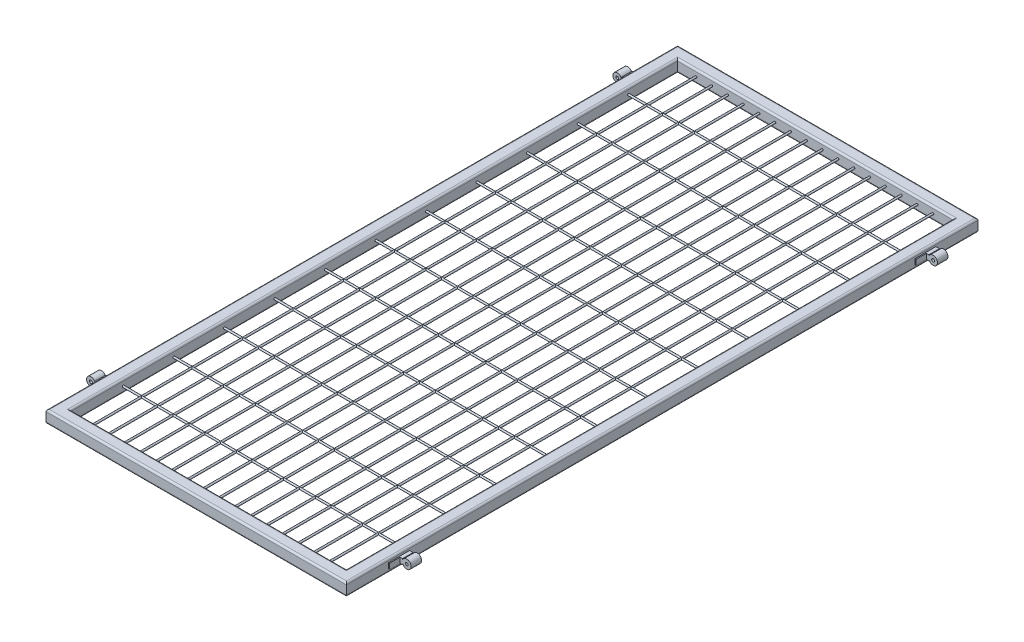
SolidWorks part; units mm, degrees
ref_plane "前视" through (0, 0, 0) normal (0, 0, 1) x (1, 0, 0)
ref_plane "上视" through (0, 0, 0) normal (0, 1, 0) x (1, 0, 0)
ref_plane "右视" through (0, 0, 0) normal (1, 0, 0) x (0, 0, -1)
sketch "草图1" plane through (0, 0, 0) normal (0, 1, 0) x (1, 0, 0)
  line L0 (0, 0) -> (0, 53.9013) construction
  line L1 (-428, 900) -> (428, 900)
  line L2 (-428, 900) -> (-428, -900)
  line L3 (-428, -900) -> (428, -900)
  line L4 (428, 900) -> (428, -900)
  line L5 (0, 0) -> (50.2306, 0) construction
  line L6 (-393, 865) -> (393, 865)
  line L7 (393, 865) -> (393, -865)
  line L8 (-393, -865) -> (393, -865)
  line L9 (-393, 865) -> (-393, -865)
  dimension "D1" = 856
  dimension "D2" = 1800
  dimension "D3" = 35
extrude "凸台-拉伸1" add sketch "草图1" along normal blind 35
ref_plane "基准面1" through (0, 17.5, 0) normal (0, 1, 0) x (1, 0, 0)
sketch "草图2" plane through (0, 17.5, 0) normal (0, 1, 0) x (1, 0, 0)
  line L0 (-428, 900) -> (-428, -900) construction
  line L1 (-428, 780) -> (-428, 720)
  line L2 (-428, 720) -> (-431, 720)
  line L3 (-431, 720) -> (-431, 750)
  line L4 (-431, 750) -> (-438, 750)
  line L5 (-438, 750) -> (-438, 780)
  line L6 (-438, 780) -> (-428, 780)
  line L7 (428, 900) -> (-428, 900) construction
  dimension "D1" = 3
  dimension "D2" = 10
  dimension "D3" = 30
  dimension "D4" = 60
  dimension "D5" = 120
extrude "凸台-拉伸2" add sketch "草图2" along normal mid plane 15
sketch "草图3" plane through (0, 0, -780) normal (0, 0, -1) x (-1, 0, 0)
  line L0 (438, 17.5) -> (354.4234, 17.5) construction
  line L1 (438, 25) -> (438, 10) construction
  line L2 (338.25, 17.5) -> (-338.25, 17.5) construction
  circle A0 centre (450, 17.5) radius 12.5
  dimension "D1" = 25
  dimension "D2" = 12
extrude "凸台-拉伸3" add sketch "草图3" against normal blind 30
sketch "草图4" plane through (0, 0, -750) normal (0, 0, 1) x (1, 0, 0)
  circle A0 centre (-450, 17.5) radius 4
  dimension "D1" = 8
extrude "切除-拉伸1" cut sketch "草图4" against normal blind 30
pattern_linear "阵列(线性)1" count 2 spacing 1500 along (0, 0, 1) of "切除-拉伸1", "凸台-拉伸2", "凸台-拉伸3"
fillet "圆角1" radius 5 16 edges at (0, 35, 900) (0, 0, 900) (428, 35, 0) (428, 0, 0) (0, 35, -900) (0, 0, -900) (-428, 0, 0) (-428, 35, 0) (0, 0, 865) (0, 35, 865) (393, 0, 0) (393, 35, 0) (0, 0, -865) (0, 35, -865) (-393, 0, 0) (-393, 35, 0)
ref_plane "基准面2" through (0, 0, 0) normal (-1, 0, 0) x (0, 0, 1)
mirror "镜向1" about plane through (0, 0, 0) normal (-1, 0, 0) of "凸台-拉伸2", "切除-拉伸1", "凸台-拉伸3", "阵列(线性)1"
sketch "草图5" plane through (-393, 0, 0) normal (1, 0, 0) x (0, 0, -1)
  line L0 (865, 30) -> (865, 5) construction
  line L1 (865, 17.5) -> (620.961, 17.5) construction
  circle A0 centre (725, 17.5) radius 2.5
  dimension "D1" = 5
  dimension "D2" = 140
extrude "凸台-拉伸4" add sketch "草图5" along normal up to surface (786 mm away) up to face at (393, 17.5, 0)
pattern_linear "阵列(线性)2" count 11 spacing 144 along (0, 0, 1) of "凸台-拉伸4"
sketch "草图6" plane through (0, 0, -865) normal (0, 0, 1) x (1, 0, 0)
  line L0 (-393, 30) -> (-393, 5) construction
  line L1 (-393, 17.5) -> (-189.048, 17.5) construction
  circle A0 centre (-340.5, 17.5) radius 2.5
  dimension "D1" = 5
  dimension "D2" = 52.5
extrude "凸台-拉伸5" add sketch "草图6" along normal up to surface (1730 mm away) up to face at (0, 17.5, 865)
pattern_linear "阵列(线性)3" count 16 spacing 45 along (1, 0, 0) of "凸台-拉伸5"
